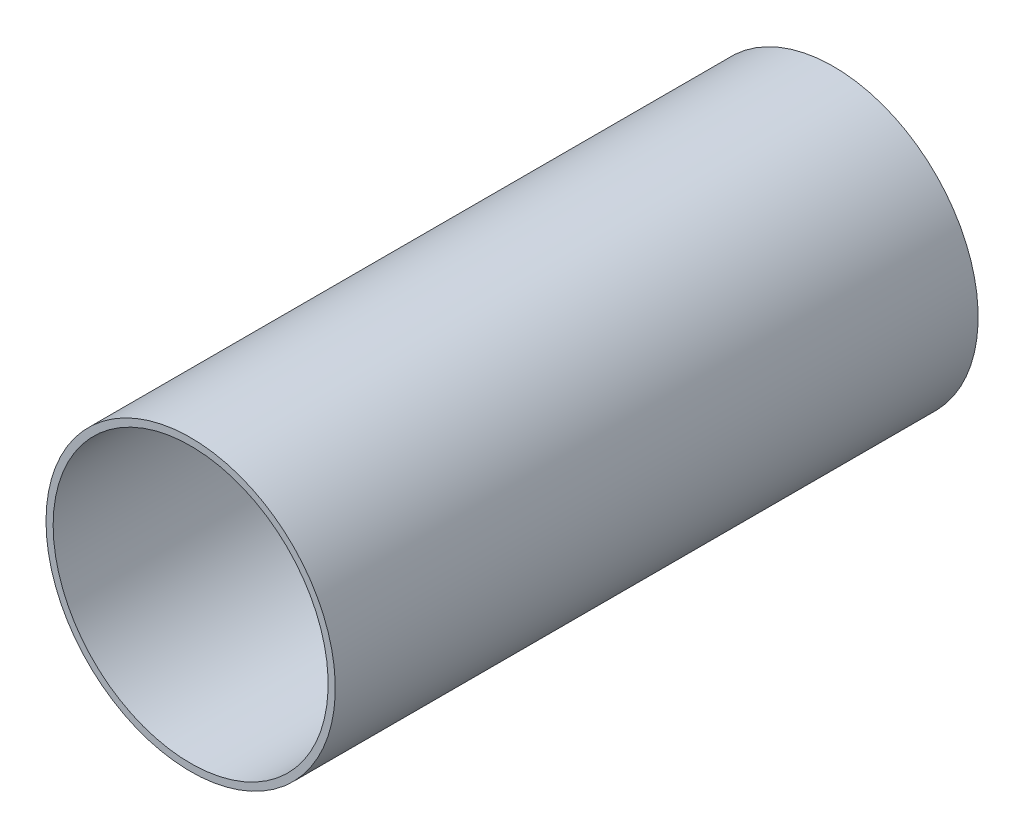
SolidWorks part; units mm, degrees
ref_plane "Front Plane" through (0, 0, 0) normal (0, 0, 1) x (1, 0, 0)
ref_plane "Top Plane" through (0, 0, 0) normal (0, 1, 0) x (1, 0, 0)
ref_plane "Right Plane" through (0, 0, 0) normal (1, 0, 0) x (0, 0, -1)
sketch "Sketch1" plane through (0, 0, 0) normal (0, 0, 1) x (1, 0, 0)
  circle A0 centre (0, 0) radius 20.25
  circle A1 centre (0, 0) radius 19.25
  dimension "D1" = 38.5
  dimension "D2" = 40.5
extrude "Boss-Extrude1" add sketch "Sketch1" along normal blind 90
